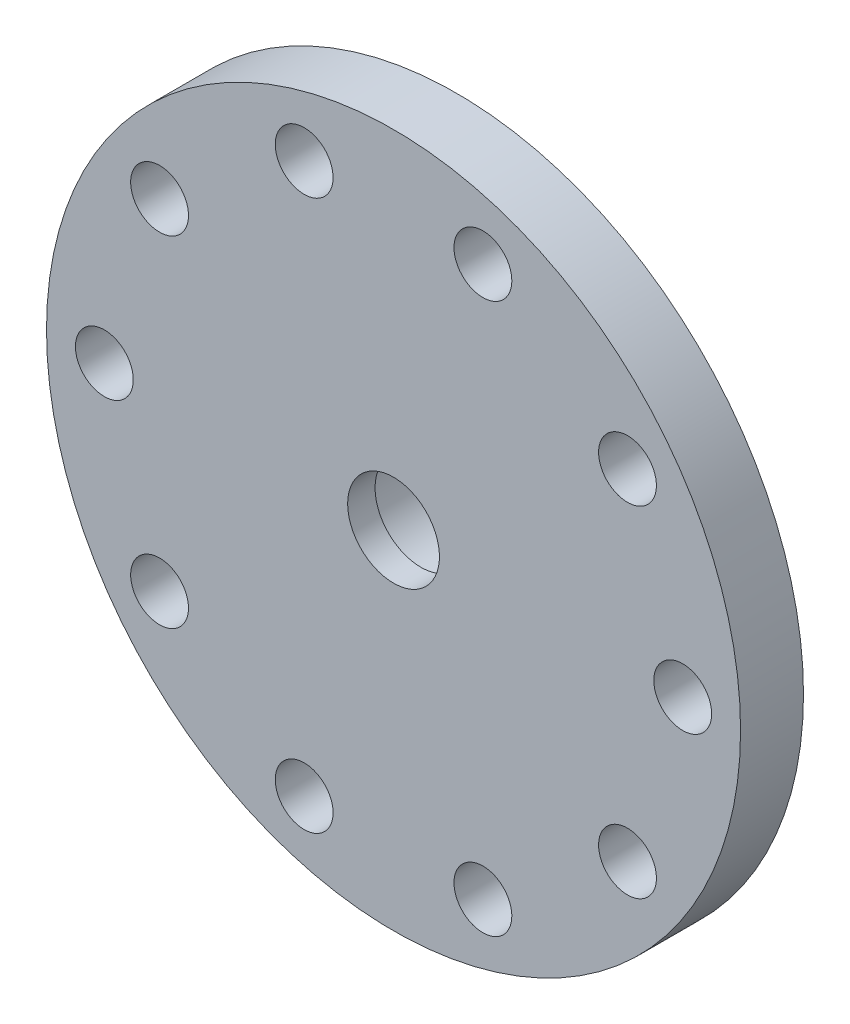
SolidWorks part; units mm, degrees
ref_plane "Front Plane" through (0, 0, 0) normal (0, 0, 1) x (1, 0, 0)
ref_plane "Top Plane" through (0, 0, 0) normal (0, 1, 0) x (1, 0, 0)
ref_plane "Right Plane" through (0, 0, 0) normal (1, 0, 0) x (0, 0, -1)
sketch "Sketch1" plane through (0, 0, 0) normal (0, 1, 0) x (1, 0, 0)
  line L0 (0, 0) -> (-30, 0)
  line L1 (-30, 0) -> (-30, 5.44)
  line L2 (-30, 5.44) -> (-19.39, 5.44)
  line L3 (-19.39, 5.44) -> (-19.39, 2.5283)
  line L4 (-19.39, 2.5283) -> (-12.15, 6.81)
  line L5 (-12.15, 6.81) -> (-12.15, 10.04)
  line L6 (-12.15, 10.04) -> (0, 10.04)
  line L7 (0, 10.04) -> (0, 0)
  dimension "D1" = 10.04
  dimension "D2" = 30
  dimension "D3" = 5.44
  dimension "D4" = 17.85
  dimension "D5" = 10.61
  dimension "D6" = 3.23
  dimension "D7" = 120.6
revolve "Revolve1" add sketch "Sketch1" angle 360 about L7
fillet "Fillet1" radius 1.5 1 edges at (-19.39, 0, -2.5283)
hole_wizard "Hole1" positions "Sketch2" profile "Sketch3" legacy end condition through all
sketch "Sketch2" plane through (0, 0, -5.44) normal (0, 0, -1) x (-1, 0, 0)
  point P0 (-25, 0)
  dimension "D1" = 25
sketch "Sketch3" plane through (25, 0, -5.44) normal (1, 0, 0) x (0, 1, 0)
  line L0 (0, 0) -> (0, 5.44)
  line L1 (0, 5.44) -> (2.5, 5.44)
  line L2 (2.5, 5.44) -> (2.5, 0)
  line L3 (2.5, 0) -> (0, 0)
  line L4 (0, 110) -> (0, -10) construction
  dimension "Diameter" = 5
  dimension "Depth" = 5.44
pattern_circular "CirPattern1" count 10 over 360 about axis through (0, 0, 0) along (0, 0, 1) of "Hole1"
hole_wizard "Hole2" positions "Sketch4" profile "Sketch5" legacy end condition through all
sketch "Sketch4" plane through (0, 0, -10.04) normal (0, 0, -1) x (-1, 0, 0)
  point P0 (0, 0)
sketch "Sketch5" plane through (0, 0, -10.04) normal (1, 0, 0) x (0, 1, 0)
  line L0 (0, 0) -> (0, 10.04)
  line L1 (0, 10.04) -> (3.968, 10.04)
  line L2 (3.968, 10.04) -> (3.968, 7.672)
  line L3 (3.968, 7.672) -> (4.969, 7.672)
  line L4 (4.969, 7.672) -> (4.969, 0)
  line L5 (4.969, 0) -> (0, 0)
  line L6 (0, -6.13) -> (0, 109.2824) construction
  line L7 (-3.968, 7.672) -> (-4.969, 7.672) construction
  line L8 (0, 10.04) -> (-3.968, 10.04) construction
  dimension "Diameter" = 7.936
  dimension "Depth" = 10.04
  dimension "C-Drill Diameter" = 9.938
  dimension "C-Drill Depth" = 7.672
  dimension "C-Drill Angle" = 180
hole_wizard "Hole3" positions "Sketch6" profile "Sketch7" legacy
sketch "Sketch6" plane through (0, 0, 0) normal (0, 1, 0) x (1, 0, 0)
  line L0 (12.15, 10.04) -> (-12.15, 10.04) construction
  point P0 (0, 10.04)
sketch "Sketch7" plane through (0, 0, -10.04) normal (1, 0, 0) x (0, 0, -1)
  line L0 (0, 0) -> (0, 30)
  line L1 (0, 30) -> (3, 30)
  line L2 (3, 30) -> (3, 0)
  line L3 (3, 0) -> (0, 0)
  line L4 (0, 110) -> (0, -10) construction
  dimension "Diameter" = 6
  dimension "Depth" = 30
